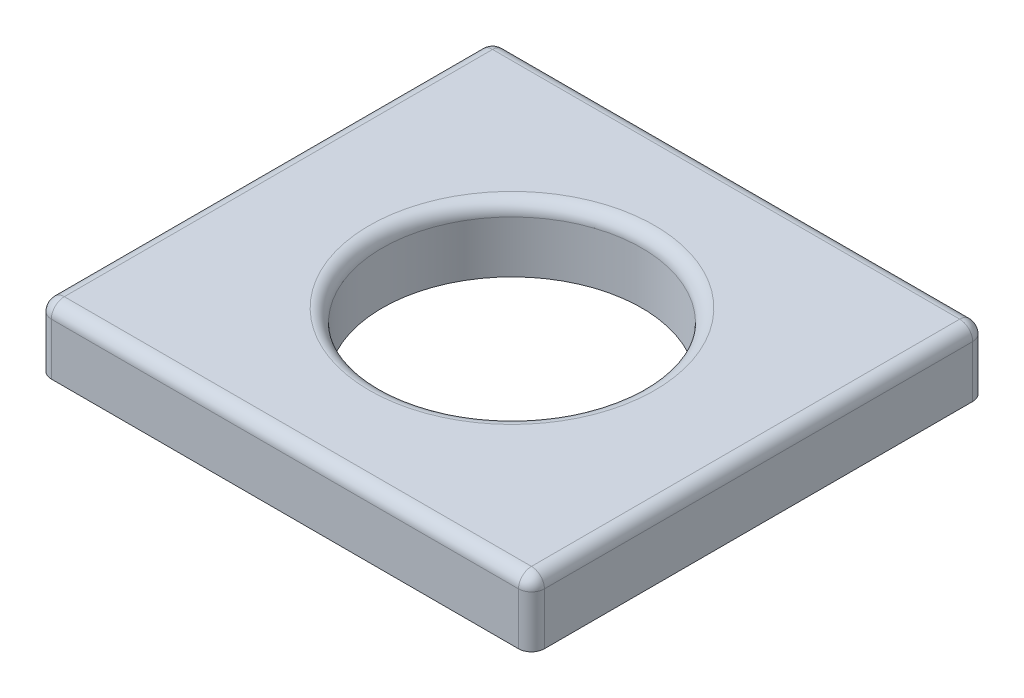
SolidWorks part; units mm, degrees
ref_plane "Front Plane" through (0, 0, 0) normal (0, 0, 1) x (1, 0, 0)
ref_plane "Top Plane" through (0, 0, 0) normal (0, 1, 0) x (1, 0, 0)
ref_plane "Right Plane" through (0, 0, 0) normal (1, 0, 0) x (0, 0, -1)
sketch "Sketch1" plane through (0, 0, 0) normal (0, 1, 0) x (1, 0, 0)
  line L1 (-3.8, 3.5) -> (3.8, 3.5)
  line L2 (-3.8, 3.5) -> (-3.8, -3.5)
  line L3 (-3.8, -3.5) -> (3.8, -3.5)
  line L4 (3.8, 3.5) -> (3.8, -3.5)
  line L5 (-3.8, 3.5) -> (3.8, -3.5) construction
  line L6 (-3.8, -3.5) -> (3.8, 3.5) construction
  point P0 (0, 0)
  dimension "D1" = 7.6
  dimension "D2" = 7
extrude "Boss-Extrude1" add sketch "Sketch1" along normal blind 1
sketch "Sketch2" plane through (0, 1, 0) normal (0, 1, 0) x (1, 0, 0)
  circle A0 centre (0, 0) radius 2
extrude "Cut-Extrude1" cut sketch "Sketch2" against normal through all
fillet "Fillet1" radius 0.2 9 edges at (0, 1, 3.5) (-3.8, 1, 0) (0, 1, -3.5) (3.8, 1, 0) (0, 1, 2) (3.8, 0.5, -3.5) (3.8, 0.5, 3.5) (-3.8, 0.5, 3.5) (-3.8, 0.5, -3.5)
